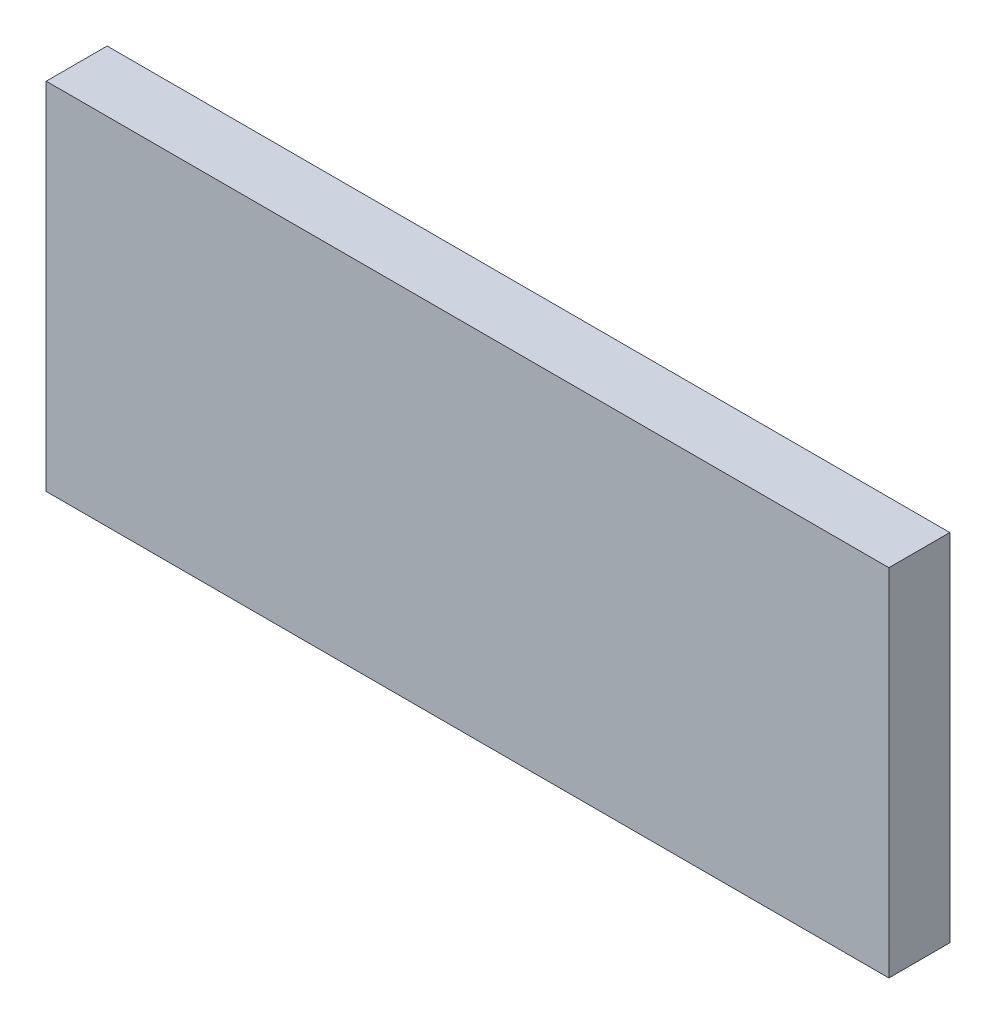
SolidWorks part; units mm, degrees
material "Pine"
ref_plane "Front Plane" through (0, 0, 0) normal (0, 0, 1) x (1, 0, 0)
ref_plane "Top Plane" through (0, 0, 0) normal (0, 1, 0) x (1, 0, 0)
ref_plane "Right Plane" through (0, 0, 0) normal (1, 0, 0) x (0, 0, -1)
sketch "Sketch3" plane through (0, 0, 0) normal (0, 0, 1) x (1, 0, 0)
  line L4 (417, 70) -> (583, 70)
  line L5 (417, 70) -> (417, 0)
  line L6 (417, 0) -> (583, 0)
  line L7 (583, 70) -> (583, 0)
  line L8 (417, 70) -> (583, 0) construction
  line L9 (417, 0) -> (583, 70) construction
  point P6 (500, 35)
  dimension "D1" = 166
  dimension "D2" = 70
extrude "Boss-Extrude2" add sketch "Sketch3" along normal blind 12 separate body
equation "\"LENGTH\" = 1000mm"
equation "\"PLY\"= 12mm"
equation "\"CENTER_BRACE_LENGTH\" = 393mm"
equation "\"PANEL_WIDTH\"= \"LENGTH\" - \"CENTER_BRACE_LENGTH\" * 2 - \"PLY\" * 4"
equation "\"D1@Boss-Extrude2\"=\"PLY\""
equation "\"D1@Sketch3\"=\"PANEL_WIDTH\""
equation "\"PANEL_SMALL_HEIGHT\" = 70mm"
equation "\"D2@Sketch3\"=\"PANEL_SMALL_HEIGHT\""
equation "\"WIDTH\" = 300mm"
